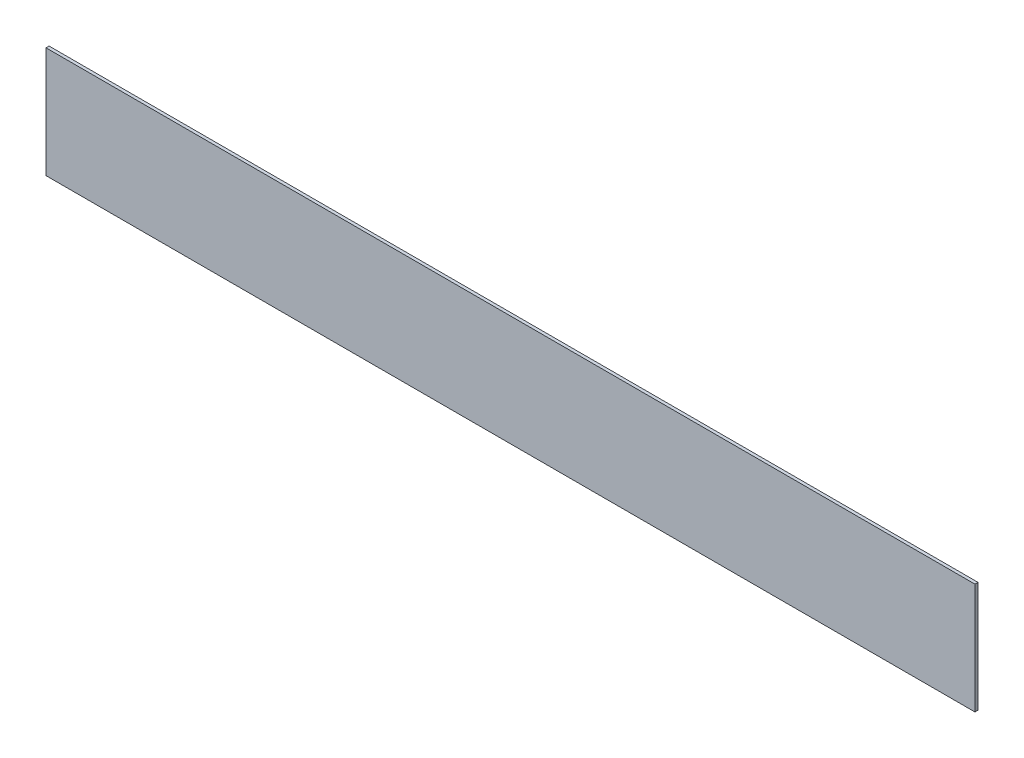
SolidWorks part; units mm, degrees
ref_plane "Front Plane" through (0, 0, 0) normal (0, 0, 1) x (1, 0, 0)
ref_plane "Top Plane" through (0, 0, 0) normal (0, 1, 0) x (1, 0, 0)
ref_plane "Right Plane" through (0, 0, 0) normal (1, 0, 0) x (0, 0, -1)
other "Configuration Table"
sketch "Sketch1" plane through (0, 0, 0) normal (0, 0, 1) x (1, 0, 0)
  line L1 (158, 57) -> (460, 57)
  line L2 (158, 57) -> (158, 93)
  line L3 (158, 93) -> (460, 93)
  line L4 (460, 57) -> (460, 93)
extrude "CEK_icecek_kulp_cukuru_1.0_1" add sketch "Sketch1" along normal blind 1 from offset 26 separate body
